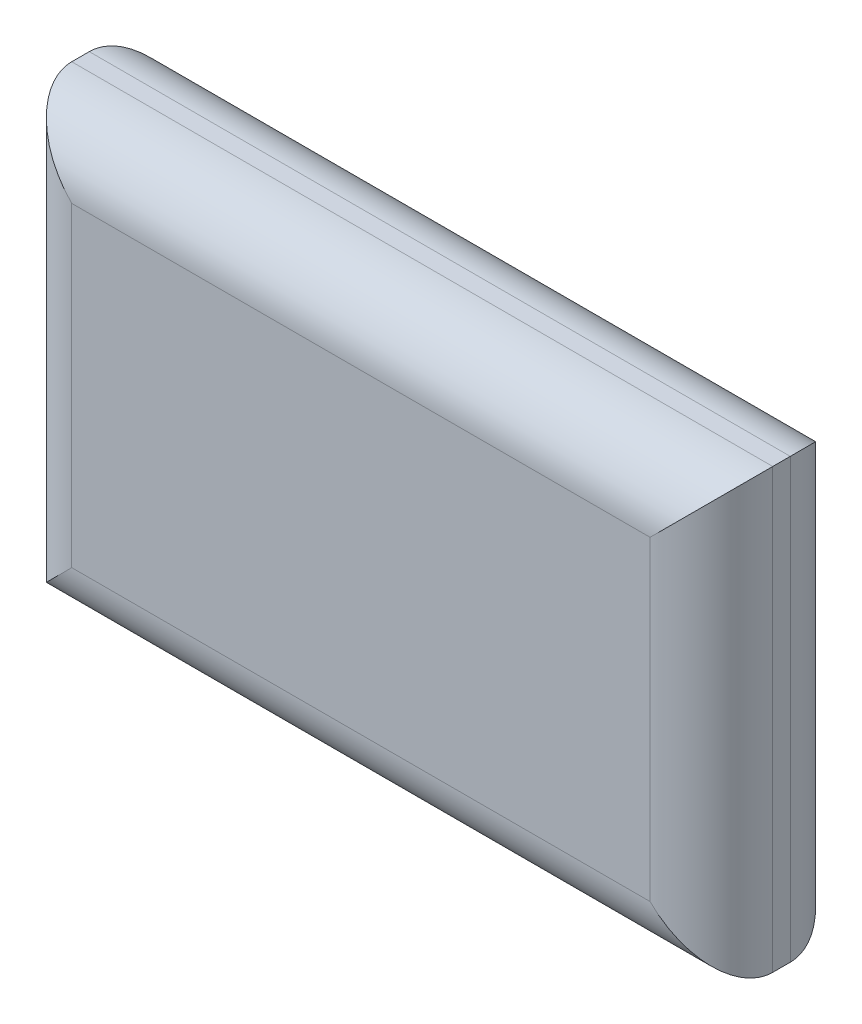
SolidWorks part; units mm, degrees
ref_plane "Plano frontal" through (0, 0, 0) normal (0, 0, 1) x (1, 0, 0)
ref_plane "Plano superior" through (0, 0, 0) normal (0, 1, 0) x (1, 0, 0)
ref_plane "Plano direito" through (0, 0, 0) normal (1, 0, 0) x (0, 0, -1)
sketch "Esboço1" plane through (0, 0, 0) normal (0, 0, 1) x (1, 0, 0)
  line L1 (-20, -12.5) -> (20, -12.5)
  line L2 (-20, -12.5) -> (-20, 12.5)
  line L3 (-20, 12.5) -> (20, 12.5)
  line L4 (20, -12.5) -> (20, 12.5)
  line L5 (-20, -12.5) -> (20, 12.5) construction
  line L6 (-20, 12.5) -> (20, -12.5) construction
  point P0 (0, 0)
  dimension "D1" = 40
  dimension "D2" = 25
extrude "Ressalto-extrusão1" add sketch "Esboço1" along normal blind 8
fillet "Filete1" radius 3.5 8 edges at (0, 12.5, 0) (-20, 0, 0) (0, -12.5, 0) (20, 0, 0) (0, -12.5, 8) (-20, 0, 8) (0, 12.5, 8) (20, 0, 8)
sketch "Esboço2" plane through (0, -12.5, 0) normal (0, -1, 0) x (1, 0, 0)
  line L0 (-20, 4) -> (20, 4) construction
  line L1 (-20, 4.5) -> (-20, 3.5) construction
  line L2 (20, 4.5) -> (20, 3.5) construction
  circle A0 centre (-19.2, 4.75) radius 0.5
  circle A1 centre (-19.2, 3.25) radius 0.5
  dimension "D1" = 1
  dimension "D2" = 0.75
  dimension "D3" = 0.8
extrude "Corte-extrusão1" cut sketch "Esboço2" against normal blind 2
